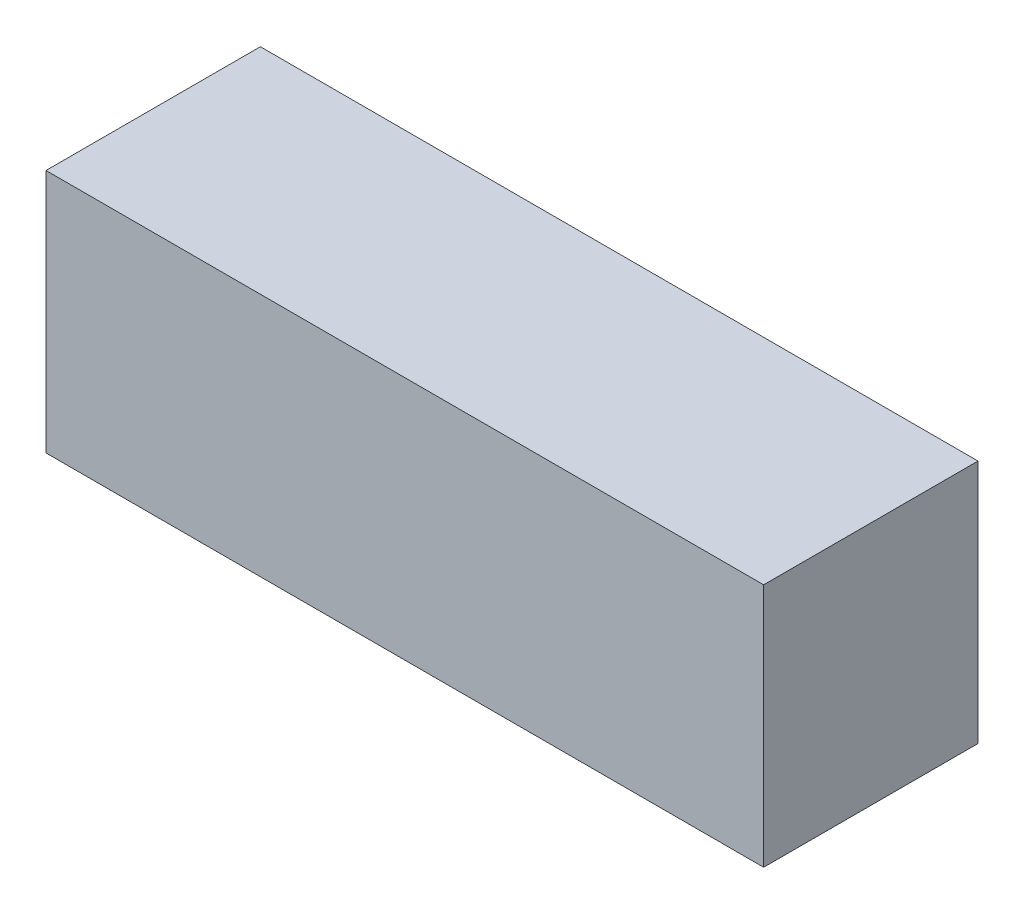
SolidWorks part; units mm, degrees
ref_plane "前视基准面" through (0, 0, 0) normal (0, 0, 1) x (1, 0, 0)
ref_plane "上视基准面" through (0, 0, 0) normal (0, 1, 0) x (1, 0, 0)
ref_plane "右视基准面" through (0, 0, 0) normal (1, 0, 0) x (0, 0, -1)
other "Configuration Table"
sketch "草图2" plane through (0, 0, 0) normal (1, 0, 0) x (0, 0, -1)
  line L1 (-23, -26.25) -> (23, -26.25)
  line L2 (-23, -26.25) -> (-23, 26.25)
  line L3 (-23, 26.25) -> (23, 26.25)
  line L4 (23, -26.25) -> (23, 26.25)
  line L5 (-23, -26.25) -> (23, 26.25) construction
  line L6 (-23, 26.25) -> (23, -26.25) construction
  point P0 (0, 0)
  dimension "D1" = 46
  dimension "D2" = 52.5
extrude "凸台-拉伸1" add sketch "草图2" along normal blind 154
